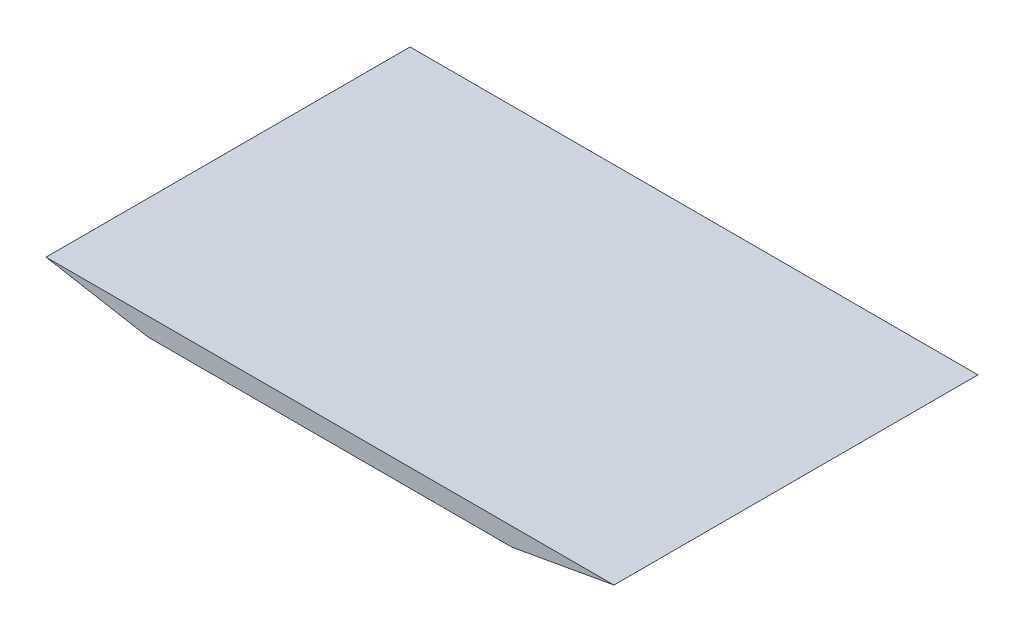
SolidWorks part; units mm, degrees
ref_plane "Front Plane" through (0, 0, 0) normal (0, 0, 1) x (1, 0, 0)
ref_plane "Top Plane" through (0, 0, 0) normal (0, 1, 0) x (1, 0, 0)
ref_plane "Right Plane" through (0, 0, 0) normal (1, 0, 0) x (0, 0, -1)
sketch "Sketch1" plane through (0, 0, 0) normal (0, 0, 1) x (1, 0, 0)
  line L0 (0, 0) -> (156, 0)
  line L1 (156, 0) -> (128, -5)
  line L2 (128, -5) -> (28, -5)
  line L3 (28, -5) -> (0, 0)
  dimension "D1" = 100
  dimension "D2" = 5
  dimension "D3" = 28
  dimension "D4" = 28
extrude "Boss-Extrude1" add sketch "Sketch1" along normal blind 100
